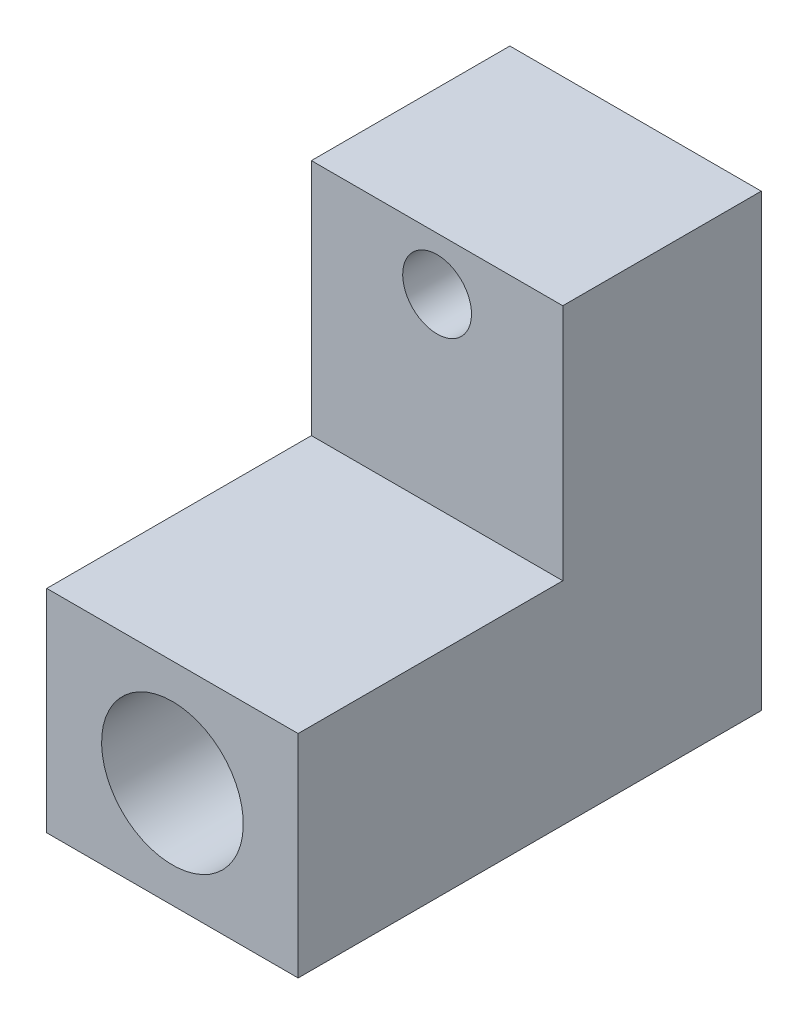
SolidWorks part; units mm, degrees
ref_plane "Front Plane" through (0, 0, 0) normal (0, 0, 1) x (1, 0, 0)
ref_plane "Top Plane" through (0, 0, 0) normal (0, 1, 0) x (1, 0, 0)
ref_plane "Right Plane" through (0, 0, 0) normal (1, 0, 0) x (0, 0, -1)
sketch "Sketch1" plane through (0, 0, 0) normal (1, 0, 0) x (0, 0, -1)
  line L0 (0, 0) -> (0, 10.16)
  line L1 (0, 10.16) -> (12.7, 10.16)
  line L2 (12.7, 10.16) -> (12.7, 21.59)
  line L3 (12.7, 21.59) -> (22.225, 21.59)
  line L4 (22.225, 21.59) -> (22.225, 0)
  line L5 (22.225, 0) -> (0, 0)
  dimension "D1" = 10.16
  dimension "D2" = 12.7
  dimension "D3" = 9.525
  dimension "D4" = 21.59
extrude "Boss-Extrude1" add sketch "Sketch1" against normal blind 12.065
hole_wizard "Tap Drill for M8x1.25 Tap1" positions "Sketch4" profile "Sketch5" hole size "M8x1.25" standard "ANSI Metric" end condition through all
sketch "Sketch4" plane through (-0.7032, 1.5474, -22.225) normal (0, 0, 1) x (1, 0, 0)
  line L8 (0.7032, -1.5474) -> (0.7032, 8.6126)
  line L9 (0.7032, 8.6126) -> (-11.3618, 8.6126)
  line L10 (-11.3618, 8.6126) -> (-11.3618, -1.5474)
  line L11 (-11.3618, -1.5474) -> (0.7032, -1.5474)
  line L13 (0.7032, 8.6126) -> (-11.3618, 8.6126) construction
  line L16 (0.7032, 8.6126) -> (-11.3618, -1.5474) construction
  line L18 (0.7032, -1.5474) -> (-11.3618, 8.6126) construction
  point P0 (-5.3293, 3.5326)
  dimension "D1" = 0
sketch "Sketch5" plane through (-6.0325, 5.08, -22.225) normal (1, 0, 0) x (0, 1, 0)
  line L0 (0, 0) -> (0, 22.225)
  line L1 (0, 22.225) -> (3.4, 22.225)
  line L2 (3.4, 22.225) -> (3.4, 0)
  line L5 (3.4, 0) -> (0, 0)
  line L11 (0, -6.35) -> (0, 107.95) construction
  dimension "Thru Hole Dia." = 6.8
  dimension "Thru Hole Depth" = 22.225
sketch "Sketch6" plane through (0, 0, -22.225) normal (0, 0, -1) x (-1, 0, 0)
  line L0 (12.065, 0) -> (12.065, 21.59) construction
  line L1 (0, 0) -> (0, 21.59) construction
  line L2 (12.065, 19.05) -> (0, 19.05) construction
  line L4 (12.065, 0) -> (0, 0) construction
  circle A0 centre (6.0325, 19.05) radius 1.651
  dimension "D2" = 3.302
  dimension "D1" = 19.05
extrude "Cut-Extrude2" cut sketch "Sketch6" against normal through all
